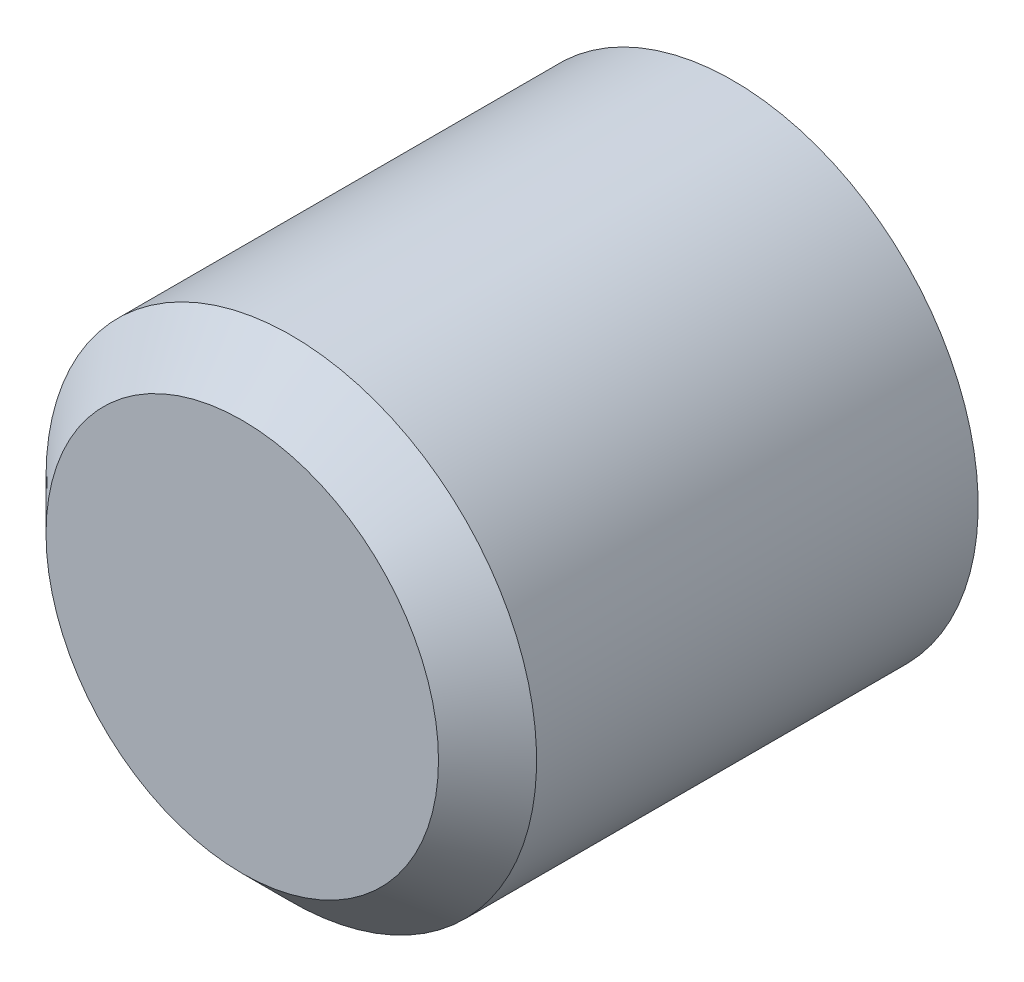
SolidWorks part; units mm, degrees
ref_plane "Front Plane" through (0, 0, 0) normal (0, 0, 1) x (1, 0, 0)
ref_plane "Top Plane" through (0, 0, 0) normal (0, 1, 0) x (1, 0, 0)
ref_plane "Right Plane" through (0, 0, 0) normal (1, 0, 0) x (0, 0, -1)
ref_plane "plane:profile-xz" through (0, 0, 0) normal (0, -1, 0) x (1, 0, 0)
sketch "sketch:main-profile" plane through (0, 0, 0) normal (0, -1, 0) x (1, 0, 0)
  line L0 (0, 0) -> (10, 0)
  line L1 (10, 0) -> (10, 18)
  line L2 (10, 18) -> (8, 20)
  line L3 (8, 20) -> (0, 20)
  line L4 (0, 20) -> (0, 0)
  line L5 (0, -5) -> (0, 25) construction
revolve "feature:chamfer-profile" add sketch "sketch:main-profile" angle 360 about L5
